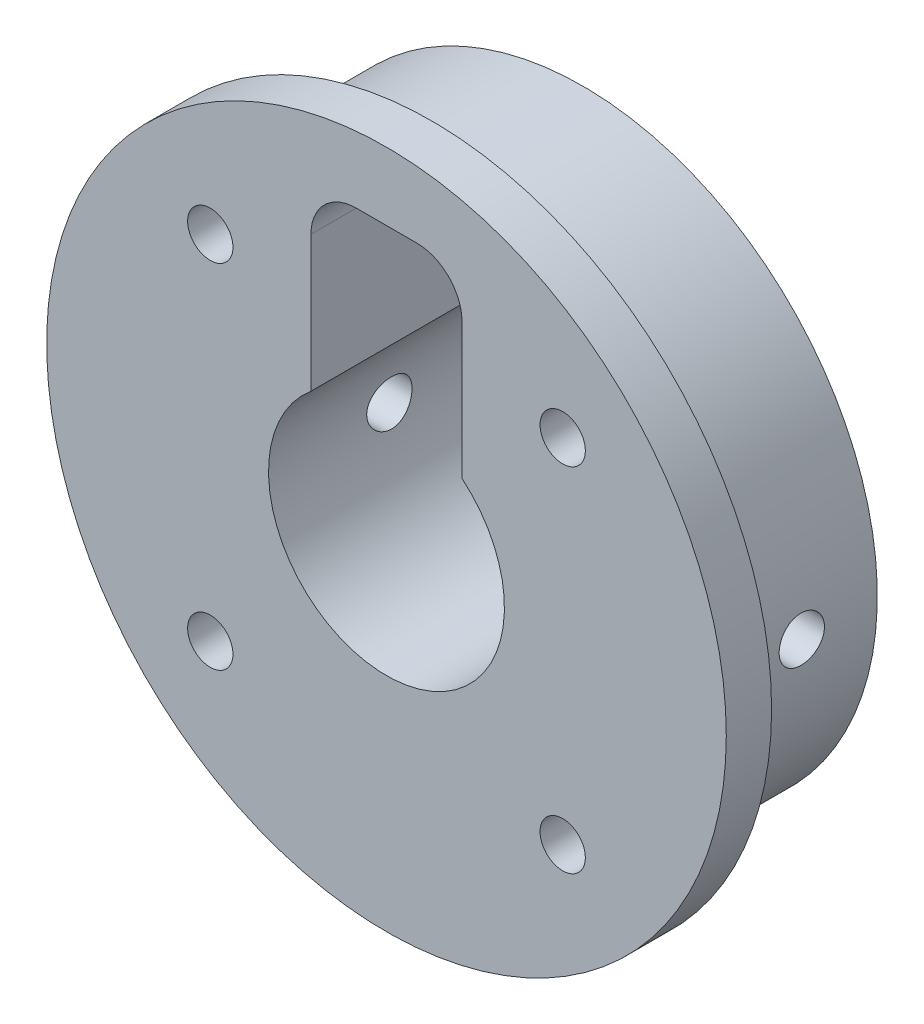
SolidWorks part; units mm, degrees
ref_plane "Front Plane" through (0, 0, 0) normal (0, 0, 1) x (1, 0, 0)
ref_plane "Top Plane" through (0, 0, 0) normal (0, 1, 0) x (1, 0, 0)
ref_plane "Right Plane" through (0, 0, 0) normal (1, 0, 0) x (0, 0, -1)
sketch "Sketch1" plane through (0, 0, 0) normal (0, 0, 1) x (1, 0, 0)
  circle A2 centre (750, 29.3136) radius 22.5
extrude "Boss-Extrude1" add sketch "Sketch1" along normal blind 3
sketch "Sketch2" plane through (0, 0, 0) normal (0, 0, -1) x (-1, 0, 0)
  circle A2 centre (-750, 29.3136) radius 19.5
  circle A3 centre (-750, 29.3136) radius 19.5
  dimension "D1" = 3
extrude "Boss-Extrude2" add sketch "Sketch2" along normal blind 10
sketch "Sketch3" plane through (0, 0, 3) normal (0, 0, 1) x (1, 0, 0)
  line L0 (750, 6.8136) -> (750, 29.3136) construction
  line L1 (750, 29.3136) -> (772.5, 29.3136) construction
  line L2 (750, 29.3136) -> (761.6673, 17.6464) construction
  line L4 (748, 47.3136) -> (752, 47.3136)
  line L5 (745, 44.3136) -> (745, 35.3136)
  line L7 (755, 44.3136) -> (755, 35.3136)
  circle A0 centre (750, 29.3136) radius 16.5 construction
  circle A1 centre (750, 29.3136) radius 22.5 construction
  circle A2 centre (761.6673, 17.6464) radius 1.5
  circle A3 centre (738.3327, 17.6464) radius 1.5
  circle A4 centre (738.3327, 40.9809) radius 1.5
  circle A5 centre (761.6673, 40.9809) radius 1.5
  arc A6 (745, 35.3136) -> (755, 35.3136) centre (750, 29.3136) ccw
  arc A7 (752, 47.3136) -> (755, 44.3136) centre (752, 44.3136) cw
  arc A8 (748, 47.3136) -> (745, 44.3136) centre (748, 44.3136) ccw
  point P18 (750, 29.3136)
  point P22 (755, 47.3136)
  point P25 (745, 47.3136)
  dimension "D1" = 4
extrude "Cut-Extrude1" cut sketch "Sketch3" against normal up to surface (13 mm away) up to face at (730.5, 29.3136, -10)
sketch "Sketch4" plane through (745, 0, 0) normal (1, 0, 0) x (0, 0, -1)
  circle A0 centre (5, 29.3136) radius 1.5
extrude "Cut-Extrude2" cut sketch "Sketch4" against normal through all both and the other way through all
